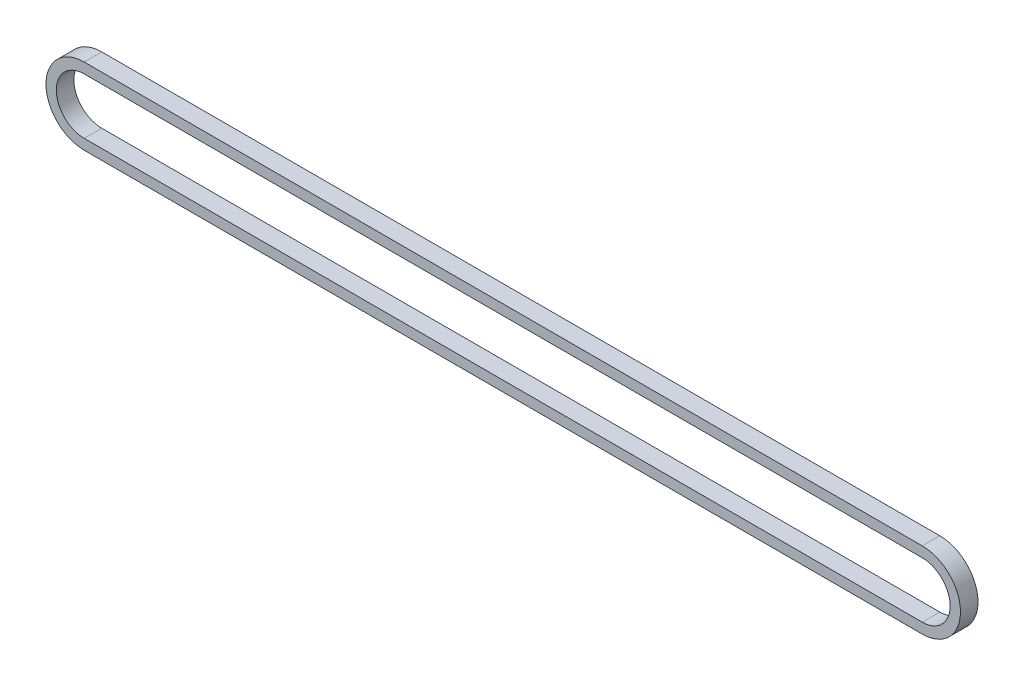
SolidWorks part; units mm, degrees
ref_plane "Front Plane" through (0, 0, 0) normal (0, 0, 1) x (1, 0, 0)
ref_plane "Top Plane" through (0, 0, 0) normal (0, 1, 0) x (1, 0, 0)
ref_plane "Right Plane" through (0, 0, 0) normal (1, 0, 0) x (0, 0, -1)
sketch "Sketch1" plane through (0, 0, 0) normal (0, 0, 1) x (1, 0, 0)
  line L0 (-203.2, 0) -> (203.2, 0) construction
  line L1 (-203.2, 18.528) -> (203.2, 18.528)
  line L2 (-203.2, -18.528) -> (203.2, -18.528)
  line L3 (-203.2, 13.5242) -> (203.2, 13.5242)
  line L4 (-203.2, -13.5242) -> (203.2, -13.5242)
  circle A0 centre (-203.2, 0) radius 18.528 construction
  circle A1 centre (203.2, 0) radius 18.528 construction
  arc A2 (-203.2, 18.528) -> (-203.2, -18.528) centre (-203.2, 0) ccw
  arc A3 (203.2, -18.528) -> (203.2, 18.528) centre (203.2, 0) ccw
  arc A4 (203.2, -13.5242) -> (203.2, 13.5242) centre (203.2, 0) ccw
  arc A5 (-203.2, 13.5242) -> (-203.2, -13.5242) centre (-203.2, 0) ccw
  point P9 (-221.728, 0)
  point P10 (221.728, 0)
  dimension "D1" = 37.0561
  dimension "D2" = 406.4
  dimension "D3" = 443.4561
  dimension "D4" = 5.0038
extrude "Boss-Extrude1" add sketch "Sketch1" along normal mid plane 8.5
